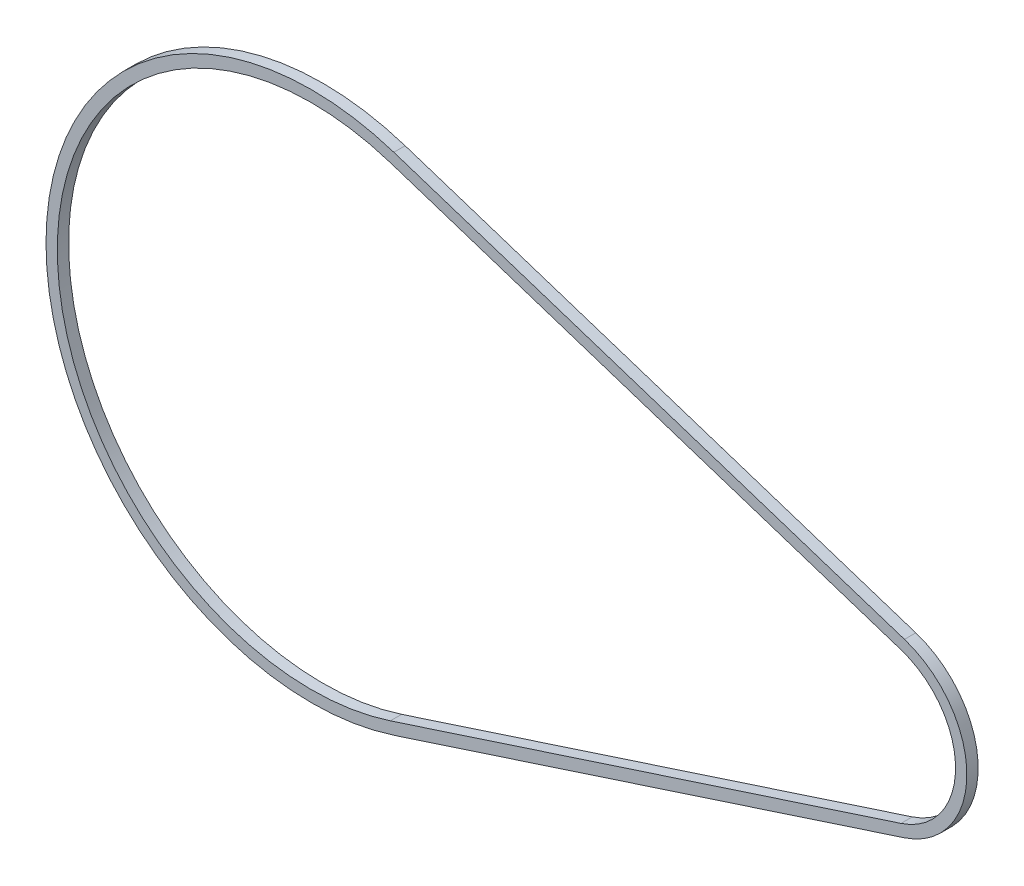
SolidWorks part; units mm, degrees
material "BUTYL"
ref_plane "Front Plane" through (0, 0, 0) normal (0, 0, 1) x (1, 0, 0)
ref_plane "Top Plane" through (0, 0, 0) normal (0, 1, 0) x (1, 0, 0)
ref_plane "Right Plane" through (0, 0, 0) normal (1, 0, 0) x (0, 0, -1)
sketch "Sketch1" plane through (0, 0, 0) normal (0, 0, 1) x (1, 0, 0)
  line L0 (0, 0) -> (500, 0) construction
  line L1 (72.85, 223.4231) -> (524.8, 76.0589)
  line L2 (72.85, -223.4231) -> (524.8, -76.0589)
  line L3 (69.75, -213.9157) -> (521.7, -66.5516)
  line L4 (69.75, 213.9157) -> (521.7, 66.5516)
  arc A0 (72.85, 223.4231) -> (72.85, -223.4231) centre (0, 0) ccw
  arc A1 (524.8, -76.0589) -> (524.8, 76.0589) centre (500, 0) ccw
  arc A2 (69.75, 213.9157) -> (69.75, -213.9157) centre (0, 0) ccw
  arc A3 (521.7, -66.5516) -> (521.7, 66.5516) centre (500, 0) ccw
  dimension "D1" = 10
  dimension "D2" = 235
  dimension "D3" = 80
  dimension "D4" = 500
extrude "Boss-Extrude2" add sketch "Sketch1" along normal blind 10
